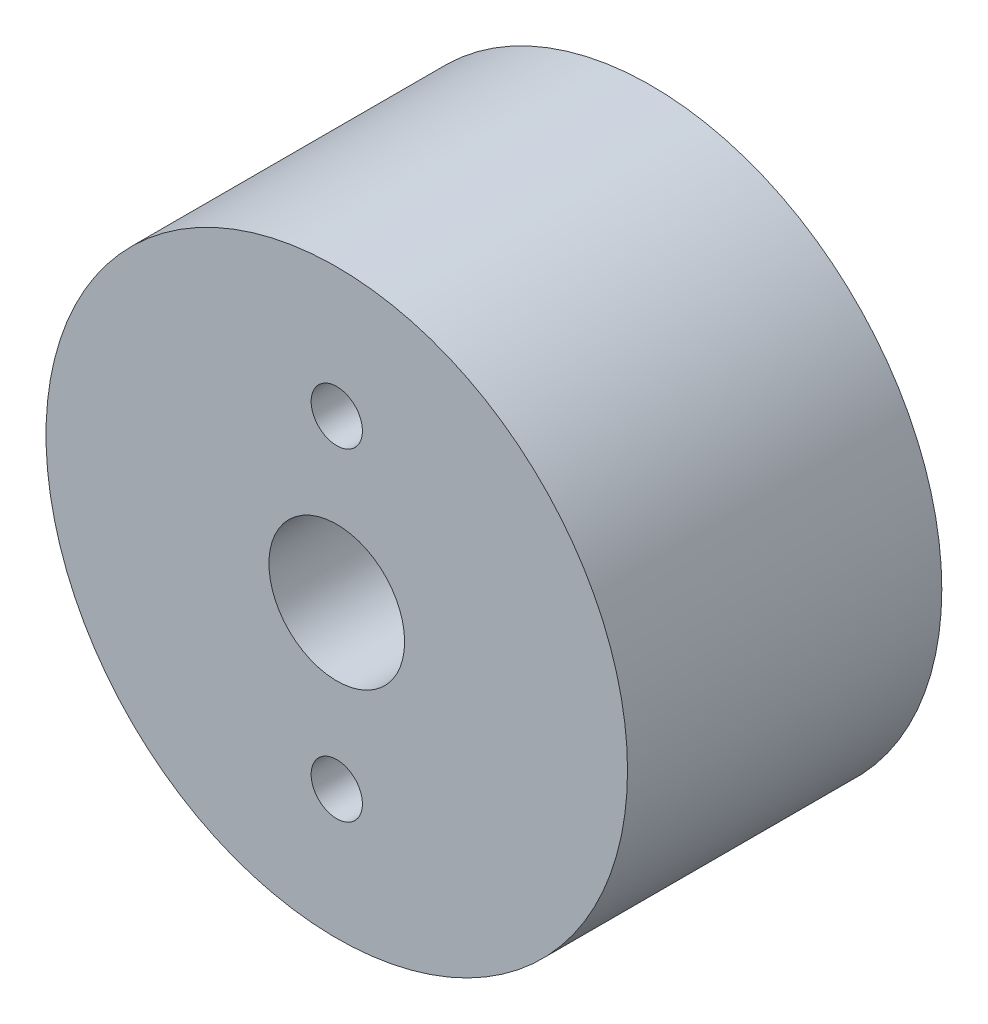
SolidWorks part; units mm, degrees
ref_plane "Front Plane" through (0, 0, 0) normal (0, 0, 1) x (1, 0, 0)
ref_plane "Top Plane" through (0, 0, 0) normal (0, 1, 0) x (1, 0, 0)
ref_plane "Right Plane" through (0, 0, 0) normal (1, 0, 0) x (0, 0, -1)
sketch "Sketch1" plane through (0, 0, 0) normal (0, 0, 1) x (1, 0, 0)
  circle A0 centre (0, 10) radius 1.5875
  circle A1 centre (0, 0) radius 18
  circle A6 centre (0, 0) radius 4.2
  circle A8 centre (0, -10) radius 1.5875
  circle A10 centre (-10, 0) radius 1.5875 [skipped]
  circle A11 centre (10, 0) radius 1.5875 [skipped]
  dimension "D1" = 4
extrude "Boss-Extrude2" add sketch "Sketch1" along normal blind 19.4564
